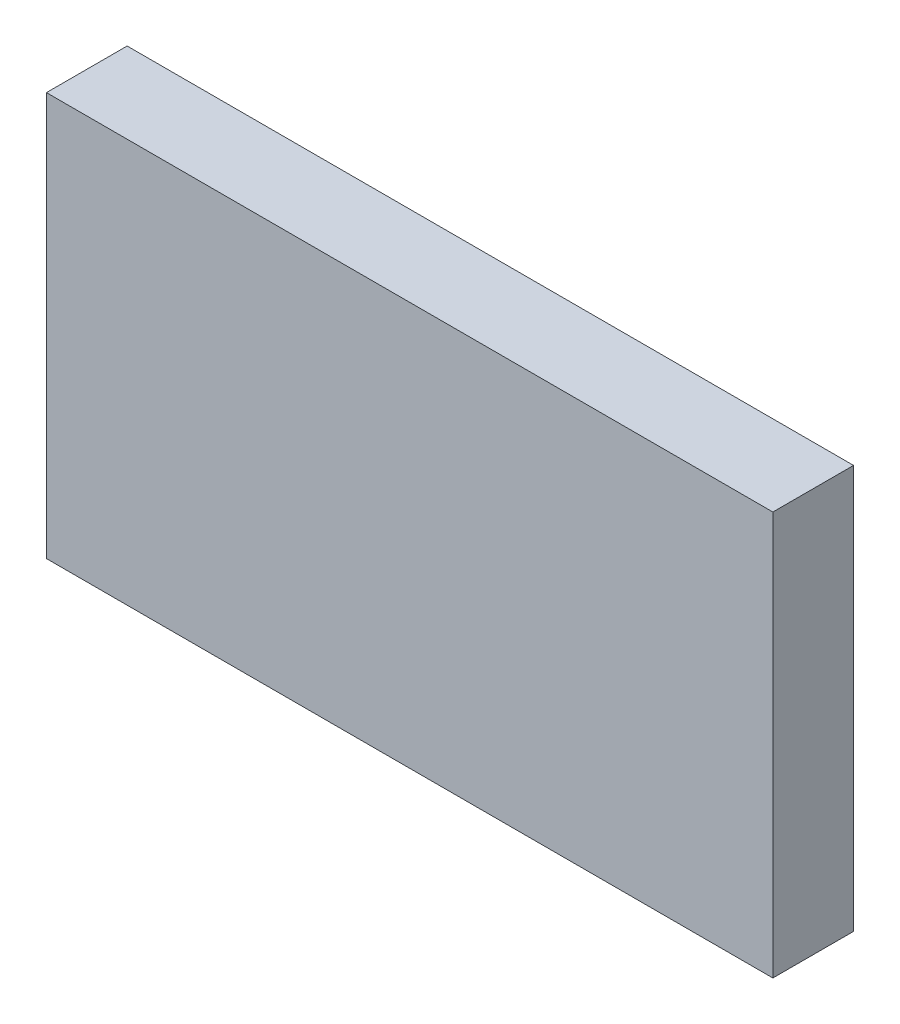
SolidWorks part; units mm, degrees
ref_plane "前视" through (0, 0, 0) normal (0, 0, 1) x (1, 0, 0)
ref_plane "上视" through (0, 0, 0) normal (0, 1, 0) x (1, 0, 0)
ref_plane "右视" through (0, 0, 0) normal (1, 0, 0) x (0, 0, -1)
sketch "Sketch1" plane through (0, 0, 0) normal (0, 0, 1) x (1, 0, 0)
  line L1 (0, 0) -> (90, 0)
  line L2 (0, 0) -> (0, 50)
  line L3 (0, 50) -> (90, 50)
  line L4 (90, 0) -> (90, 50)
  dimension "D1" = 90
  dimension "D2" = 50
extrude "Extrude1" add sketch "Sketch1" along normal blind 10
